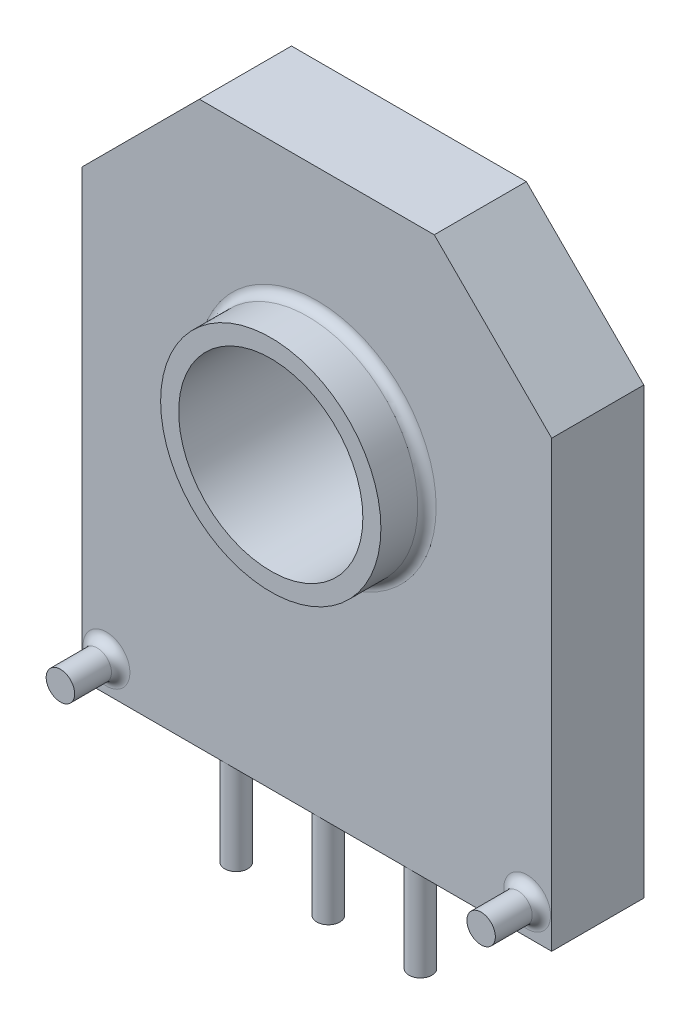
SolidWorks part; units mm, degrees
ref_plane "Front Plane" through (0, 0, 0) normal (0, 0, 1) x (1, 0, 0)
ref_plane "Top Plane" through (0, 0, 0) normal (0, 1, 0) x (1, 0, 0)
ref_plane "Right Plane" through (0, 0, 0) normal (1, 0, 0) x (0, 0, -1)
sketch "Sketch1" plane through (0, 0, 0) normal (0, 0, 1) x (1, 0, 0)
  line L0 (0, 5.6034) -> (0, -10.0149) construction
  line L1 (-4.5894, 0) -> (4.5894, 0) construction
  line L2 (0, -7.1) -> (5.1, -7.1)
  line L5 (2.55, 5.1) -> (-2.55, 5.1)
  line L6 (-2.55, 5.1) -> (-5.1, 2.55)
  line L7 (-5.1, 2.55) -> (-5.1, 0)
  line L8 (-5.1, 0) -> (-5.1, -7.1)
  line L9 (-5.1, -7.1) -> (0, -7.1)
  line L10 (5.1, 0) -> (5.1, -7.1)
  line L11 (5.1, 2.55) -> (5.1, 0)
  line L12 (2.55, 5.1) -> (5.1, 2.55)
  circle A0 centre (0, 0) radius 2
  point P12 (0, 0)
  point P15 (0, 5.1)
  dimension "D1" = 4
  dimension "D2" = 7.1
  dimension "D4" = 10.2
  dimension "D5" = 5.1
  dimension "D6" = 135
extrude "Boss-Extrude1" add sketch "Sketch1" along normal blind 2
sketch "Sketch2" plane through (0, 0, 2) normal (0, 0, 1) x (1, 0, 0)
  line L0 (0, 0) -> (0, -4.3405) construction
  circle A0 centre (0, 0) radius 2
  circle A1 centre (0, 0) radius 2.3915
  circle A2 centre (-4.5678, -6.4374) radius 0.3089
  circle A3 centre (4.5678, -6.4374) radius 0.3089
extrude "Boss-Extrude2" add sketch "Sketch2" along normal blind 1
fillet "Fillet1" radius 0.2
sketch "Sketch3" plane through (0, -7.1, 0) normal (0, -1, 0) x (1, 0, 0)
  line L0 (0, 2) -> (0, 1.5) construction
  line L1 (-5.1, 2) -> (5.1, 2) construction
  line L2 (0, 1.75) -> (2, 1.75) construction
  circle A0 centre (0, 1.75) radius 0.25
  circle A1 centre (2, 1.75) radius 0.25
  circle A2 centre (-2, 1.75) radius 0.25
  dimension "D1" = 0.5
  dimension "D3" = 2
  dimension "D2" = 2
extrude "Boss-Extrude3" add sketch "Sketch3" along normal blind 2
